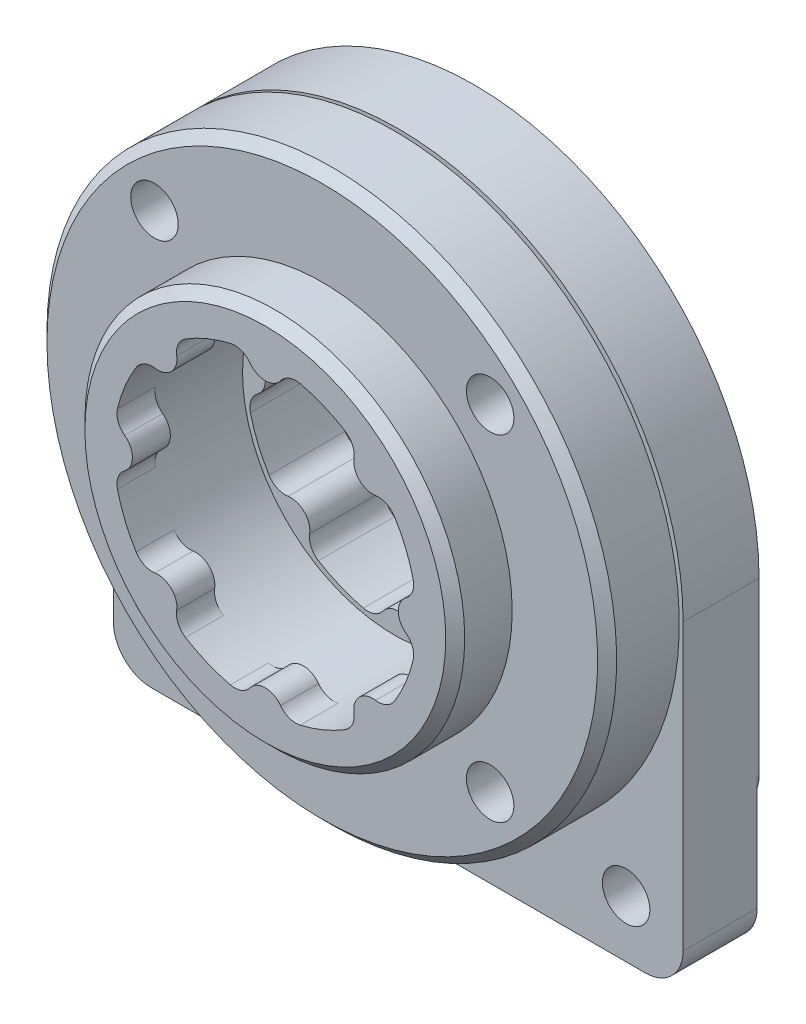
SolidWorks part; units mm, degrees
material "1060 合金"
ref_plane "前视基准面" through (0, 0, 0) normal (0, 0, 1) x (1, 0, 0)
ref_plane "上视基准面" through (0, 0, 0) normal (0, 1, 0) x (1, 0, 0)
ref_plane "右视基准面" through (0, 0, 0) normal (1, 0, 0) x (0, 0, -1)
other "Configuration Table"
sketch "草图1" plane through (0, 0, 0) normal (0, 0, 1) x (1, 0, 0)
  circle A0 centre (0, 0) radius 7
  circle A1 centre (0, 0) radius 10
  dimension "D1" = 14
  dimension "D2" = 20
extrude "凸台-拉伸1" add sketch "草图1" along normal blind 2
sketch "草图2" plane through (0, 0, 0) normal (0, 0, -1) x (-1, 0, 0)
  circle A0 centre (0, 0) radius 10
  circle A1 centre (0, 0) radius 8
  dimension "D1" = 16
  dimension "D2" = 20
extrude "凸台-拉伸2" add sketch "草图2" along normal blind 5
sketch "草图3" plane through (0, 0, 2) normal (0, 0, 1) x (1, 0, 0)
  circle A0 centre (0, 0) radius 8
  circle A1 centre (0, 8) radius 1
  circle A2 centre (0, 0) radius 7 construction
  circle A3 centre (5.6569, 5.6569) radius 1
  circle A4 centre (8, 0) radius 1
  circle A5 centre (5.6569, -5.6569) radius 1
  circle A6 centre (0, -8) radius 1
  circle A7 centre (-5.6569, -5.6569) radius 1
  circle A8 centre (-8, 0) radius 1
  circle A9 centre (-5.6569, 5.6569) radius 1
  point P24 (0, 0)
  dimension "D1" = 16
  dimension "D2" = 2
  dimension "D3" = 8
extrude "切除-拉伸2" cut sketch "草图3" against normal blind 2 contours A9 A4 A1 A0 | A9 A0 A8 A4 | A8 A0 A7 A4 | A7 A0 A6 A4 | A6 A0 A5 A4 | A5 A0 A4 | A4 A0 A3 | A3 A0 A1 A4
fillet "圆角4" radius 1 16 edges at (-0.998, 7.9375, 1) (0.998, 7.9375, 1) (-4.9069, 6.3184, 1) (-6.3184, 4.9069, 1) (-7.9375, -0.998, 1) (-7.9375, 0.998, 1) (-4.9069, -6.3184, 1) (-6.3184, -4.9069, 1) (0.998, -7.9375, 1) (-0.998, -7.9375, 1) (6.3184, -4.9069, 1) (4.9069, -6.3184, 1) (7.9375, 0.998, 1) (7.9375, -0.998, 1) (4.9069, 6.3184, 1) (6.3184, 4.9069, 1)
sketch "草图4" plane through (0, 0, -5) normal (0, 0, -1) x (-1, 0, 0)
  line L0 (0, 0) -> (0, 15) construction
  line L1 (0, 0) -> (10.6066, 10.6066) construction
  circle A0 centre (0, 0) radius 15
  circle A1 centre (0, 0) radius 10
  circle A2 centre (0, 0) radius 12.5 construction
  circle A4 centre (8.8388, 8.8388) radius 1.25
  circle A5 centre (8.8388, -8.8388) radius 1.25
  circle A6 centre (-8.8388, -8.8388) radius 1.25
  circle A7 centre (-8.8388, 8.8388) radius 1.25
  point P18 (0, 0)
  dimension "D1" = 20
  dimension "D2" = 30
  dimension "D3" = 25
  dimension "D4" = 45
  dimension "D5" = 2.5
  dimension "D6" = 4
extrude "凸台-拉伸3" add sketch "草图4" against normal blind 4
sketch "草图5" plane through (0, 0, -5) normal (0, 0, -1) x (-1, 0, 0)
  line L0 (-15, 0) -> (-15, -17)
  line L1 (-15, -17) -> (15, -17)
  line L2 (15, -17) -> (15, 0)
  circle A0 centre (0, 0) radius 15
  circle A1 centre (0, 0) radius 7 construction
  circle A2 centre (0, 0) radius 8
  circle A3 centre (0, 8) radius 1
  circle A4 centre (5.6569, 5.6569) radius 1
  circle A5 centre (8, 0) radius 1
  circle A6 centre (5.6569, -5.6569) radius 1
  circle A7 centre (0, -8) radius 1
  circle A8 centre (-5.6569, -5.6569) radius 1
  circle A9 centre (-8, 0) radius 1
  circle A10 centre (-5.6569, 5.6569) radius 1
  circle A11 centre (-8.8388, 8.8388) radius 1.5
  circle A12 centre (8.8388, 8.8388) radius 1.5
  circle A13 centre (8.8388, -8.8388) radius 1.5
  circle A14 centre (-8.8388, -8.8388) radius 1.5
  point P27 (0, 0)
  circle M17 centre (0, 0) radius 8
  circle M18 centre (-8.8388, 8.8388) radius 1.25
  circle M19 centre (-8.8388, -8.8388) radius 1.25
  circle M20 centre (8.8388, -8.8388) radius 1.25
  circle M21 centre (8.8388, 8.8388) radius 1.25
  circle M22 centre (0, 0) radius 15
  dimension "D1" = 30
  dimension "D3" = 14
  dimension "D4" = 16
  dimension "D5" = 2
  dimension "D7" = 3
  dimension "D2" = 17
  dimension "D6" = 8
extrude "凸台-拉伸4" add sketch "草图5" along normal blind 4 separate body contours A10 A2 A3 A4 A5 A6 A7 A8 A9 M22 M18 M20 M21 M19 | L1 L2 L0 M22 | A8 M17 | A8 M17 | A7 M17 | A7 M17 | A6 M17 | A6 M17 | A5 M17 | A5 M17 | A4 M17 | A4 M17 | A3 M17 | A3 M17 | A10 M17 | A10 M17 | A9 M17 | A9 M17
fillet "圆角5" radius 1 16 edges at (7.9375, 0.998, -7) (7.9375, -0.998, -7) (6.3184, -4.9069, -7) (4.9069, -6.3184, -7) (0.998, -7.9375, -7) (-0.998, -7.9375, -7) (-4.9069, -6.3184, -7) (-6.3184, -4.9069, -7) (-7.9375, -0.998, -7) (-7.9375, 0.998, -7) (-6.3184, 4.9069, -7) (-4.9069, 6.3184, -7) (-0.998, 7.9375, -7) (0.998, 7.9375, -7) (4.9069, 6.3184, -7) (6.3184, 4.9069, -7)
sketch "草图6" plane through (0, 0, -5) normal (0, 0, -1) x (-1, 0, 0)
  circle A0 centre (0, 0) radius 15
  dimension "D1" = 30
extrude "切除-拉伸3" cut sketch "草图6" against normal blind 0.2
sketch "草图7" plane through (0, 0, -9) normal (0, 0, -1) x (-1, 0, 0)
  line L0 (15, -17) -> (15, 0) construction
  line L1 (-15, -17) -> (15, -17)
  line L2 (-15, -17) -> (-15, -11)
  line L3 (-15, -11) -> (15, -11)
  line L4 (15, -17) -> (15, -11)
  dimension "D1" = 6
extrude "切除-拉伸4" cut sketch "草图7" against normal blind 0.1
fillet "圆角6" radius 2 4 edges at (15, -17, -6.95) (-15, -17, -6.95) (15, -11, -8.95) (-15, -11, -8.95)
sketch "草图8" plane through (0, 0, -8.9) normal (0, 0, -1) x (-1, 0, 0)
  line L0 (-12, -14) -> (12, -14) construction
  line L1 (15, -15) -> (15, -9) construction
  line L2 (0, -14) -> (0, -17) construction
  line L3 (-13, -17) -> (13, -17) construction
  circle A0 centre (12, -14) radius 1.25
  circle A1 centre (-12, -14) radius 1.25
  dimension "D2" = 2.5
  dimension "D1" = 3
  dimension "D3" = 3
extrude "切除-拉伸5" cut sketch "草图8" against normal blind 11
chamfer "倒角1" distance 0.5 angle 45 2 edges at (10, 0, 2) (-15, 0, -1)
sketch "草图9" plane through (0, 0, -4.8) normal (0, 0, -1) x (-1, 0, 0)
  circle A1 centre (0, 0) radius 15
  circle A2 centre (0, 0) radius 15
  dimension "D1" = 0
